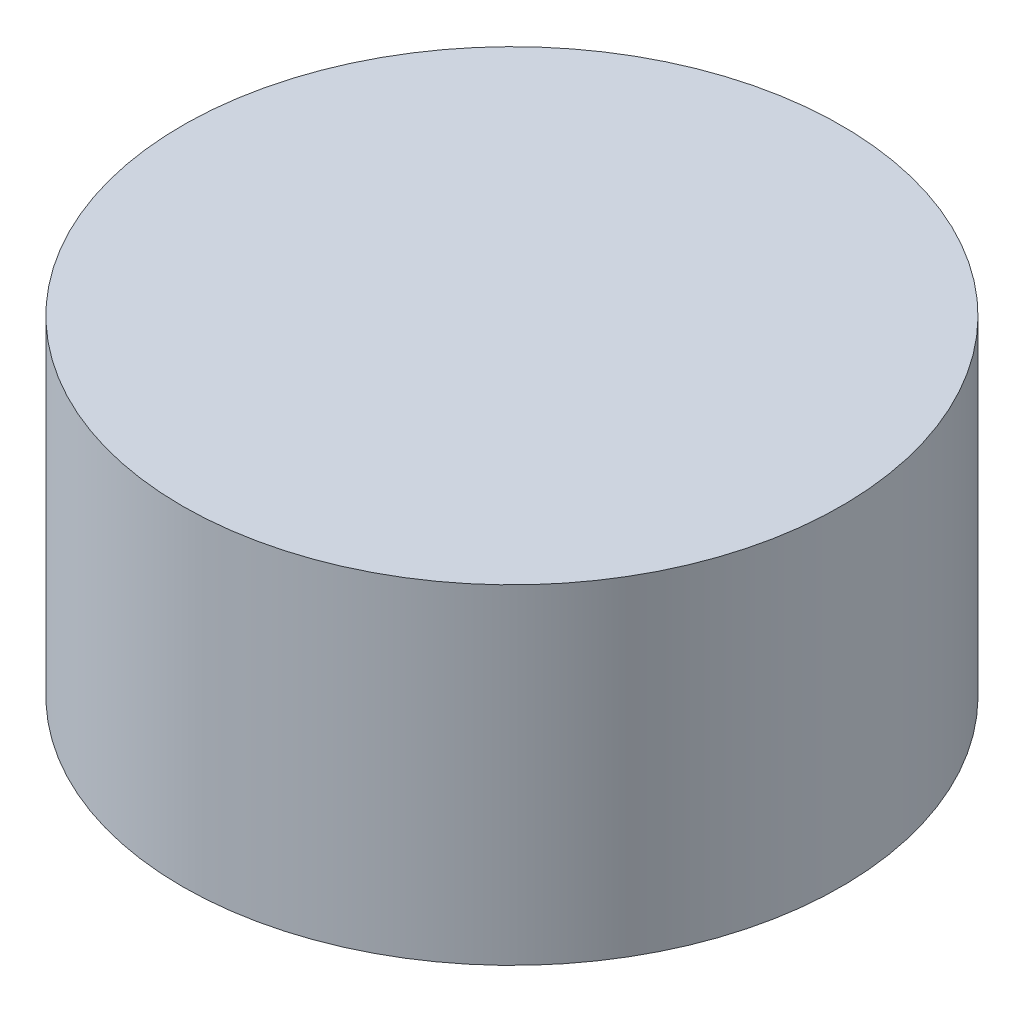
SolidWorks part; units mm, degrees
ref_plane "Front Plane" through (0, 0, 0) normal (0, 0, 1) x (1, 0, 0)
ref_plane "Top Plane" through (0, 0, 0) normal (0, 1, 0) x (1, 0, 0)
ref_plane "Right Plane" through (0, 0, 0) normal (1, 0, 0) x (0, 0, -1)
sketch "Sketch1" plane through (0, 0, 0) normal (0, 1, 0) x (1, 0, 0)
  circle A0 centre (0, 0) radius 3
  circle A1 centre (0, 0) radius 10
extrude "Boss-Extrude1" add sketch "Sketch1" along normal blind 10
sketch "Sketch2" plane through (0, 10, 0) normal (0, 1, 0) x (1, 0, 0)
  circle A0 centre (0, 0) radius 3
extrude "Boss-Extrude2" add sketch "Sketch2" against normal blind 10
